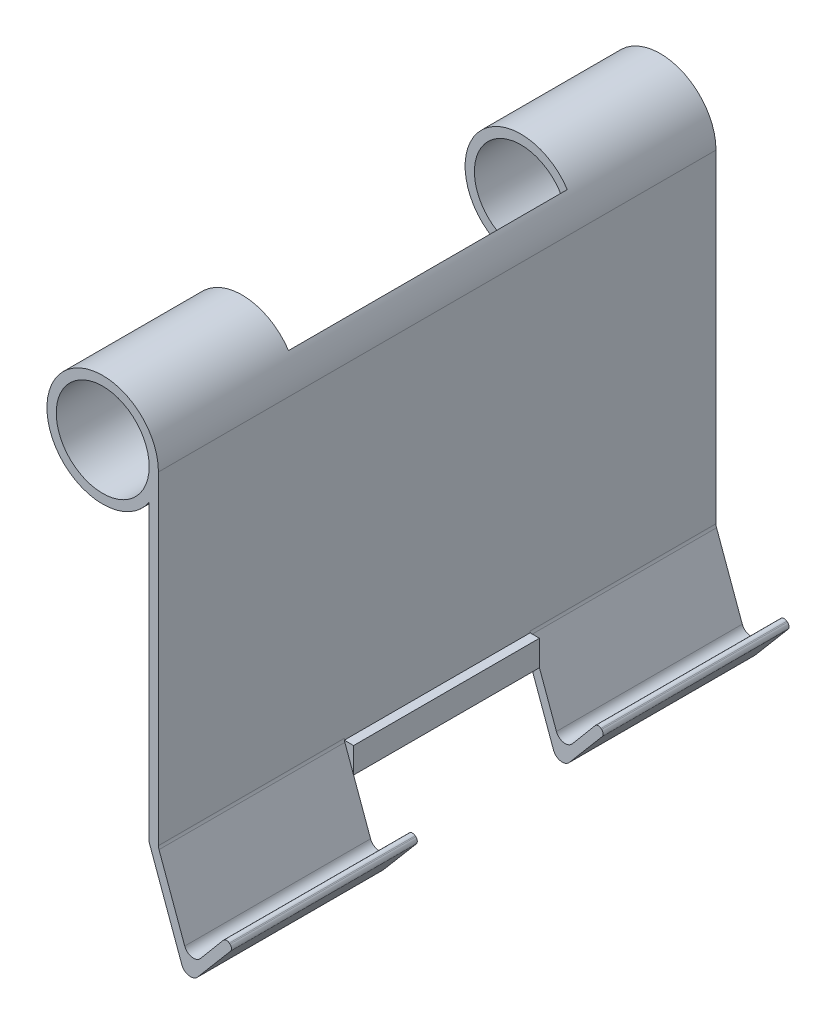
SolidWorks part; units mm, degrees
ref_plane "Front Plane" through (0, 0, 0) normal (0, 0, 1) x (1, 0, 0)
ref_plane "Top Plane" through (0, 0, 0) normal (0, 1, 0) x (1, 0, 0)
ref_plane "Right Plane" through (0, 0, 0) normal (1, 0, 0) x (0, 0, -1)
sketch "Sketch1" plane through (0, 0, 0) normal (0, 0, 1) x (1, 0, 0)
  line L0 (0, 0) -> (0, -88.9)
  line L1 (0, -88.9) -> (2.54, -88.9)
  line L2 (2.54, -88.9) -> (2.54, 0)
  line L3 (2.54, 0) -> (0, 0)
  line L4 (0, 0) -> (-12.7, 0) construction
  line L5 (2.54, -88.9) -> (11.2273, -112.7682)
  line L6 (11.2273, -112.7682) -> (21.0234, -101.0937)
  line L7 (0, -88.9) -> (10.4248, -117.5418)
  line L8 (21.0234, -101.0937) -> (22.9691, -102.7264)
  line L9 (22.9691, -102.7264) -> (10.4248, -117.5418)
  circle A0 centre (-12.7, 0) radius 12.7
  circle A1 centre (-12.7, 0) radius 15.24
  dimension "D1" = 88.9
  dimension "D2" = 2.54
  dimension "D3" = 12.7
  dimension "D4" = 160
  dimension "D5" = 60
  dimension "D6" = 25.4
  dimension "D7" = 15.24
  dimension "D8" = 30.48
  dimension "D9" = 2.54
extrude "Boss-Extrude1" add sketch "Sketch1" along normal blind 152.4 contours L3 A1 L0 A0 | L0 A1 L3 | A1 L0 L1 L2 | L9 L8 L6 L5 L1 L7
sketch "Sketch2" plane through (2.54, 0, 0) normal (1, 0, 0) x (0, 0, -1)
  line L0 (-152.4, -44.45) -> (0, -44.45) construction
  line L1 (-152.4, -88.9) -> (-152.4, 0) construction
  line L2 (0, -88.9) -> (0, 0) construction
  line L3 (-76.2, -88.9) -> (-76.2, 0) construction
  line L4 (-152.4, -88.9) -> (0, -88.9) construction
  line L5 (-152.4, 0) -> (0, 0) construction
  line L7 (-101.6, -44.45) -> (-50.8, -44.45)
  line L8 (-101.6, -44.45) -> (-101.6, -136.0466)
  line L9 (-101.6, -136.0466) -> (-50.8, -136.0466)
  line L10 (-50.8, -44.45) -> (-50.8, -136.0466)
  dimension "D1" = 25.4
  dimension "D2" = 25.4
extrude "Cut-Extrude1" cut sketch "Sketch2" along normal up to next
fillet "Fillet1" radius 2.54 6 edges at (2.54, -88.9, 127) (2.54, -88.9, 25.4) (11.2273, -112.7682, 25.4) (11.2273, -112.7682, 127) (10.4248, -117.5418, 25.4) (10.4248, -117.5418, 127)
fillet "Fillet3" radius 1.143 4 edges at (22.9691, -102.7264, 25.4) (21.0234, -101.0937, 25.4) (22.9691, -102.7264, 127) (21.0234, -101.0937, 127)
sketch "Sketch4" plane through (0, 0, 0) normal (-1, 0, 0) x (0, 0, 1)
  line L0 (0, -48.6621) -> (152.4, -48.6621) construction
  line L1 (0, -8.4242) -> (0, -88.9) construction
  line L2 (152.4, -8.4242) -> (152.4, -88.9) construction
  line L3 (76.2, -88.9) -> (76.2, 15.24) construction
  line L4 (152.4, -88.9) -> (0, -88.9) construction
  line L5 (152.4, 15.24) -> (0, 15.24) construction
  line L6 (0, -15.24) -> (152.4, -15.24) construction
  line L8 (38.1, 45.72) -> (114.3, 45.72)
  line L9 (38.1, 45.72) -> (38.1, -15.24)
  line L10 (38.1, -15.24) -> (114.3, -15.24)
  line L11 (114.3, 45.72) -> (114.3, -15.24)
  line L12 (38.1, 45.72) -> (114.3, -15.24) construction
  line L13 (38.1, -15.24) -> (114.3, 45.72) construction
  dimension "D1" = 76.2
extrude "Cut-Extrude3" cut sketch "Sketch4" along normal blind 38.1
sketch "Sketch5" plane through (2.54, 0, 0) normal (1, 0, 0) x (0, 0, -1)
  line L0 (-50.8, -88.4521) -> (-50.8, -89.3209) construction
  line L1 (-101.6, -95.8786) -> (-50.8, -95.8786)
  line L2 (-101.6, -95.8786) -> (-101.6, -88.8865)
  line L3 (-101.6, -88.8865) -> (-50.8, -88.8865)
  line L4 (-50.8, -95.8786) -> (-50.8, -88.8865)
extrude "Boss-Extrude2" add sketch "Sketch5" along normal blind 2.54
